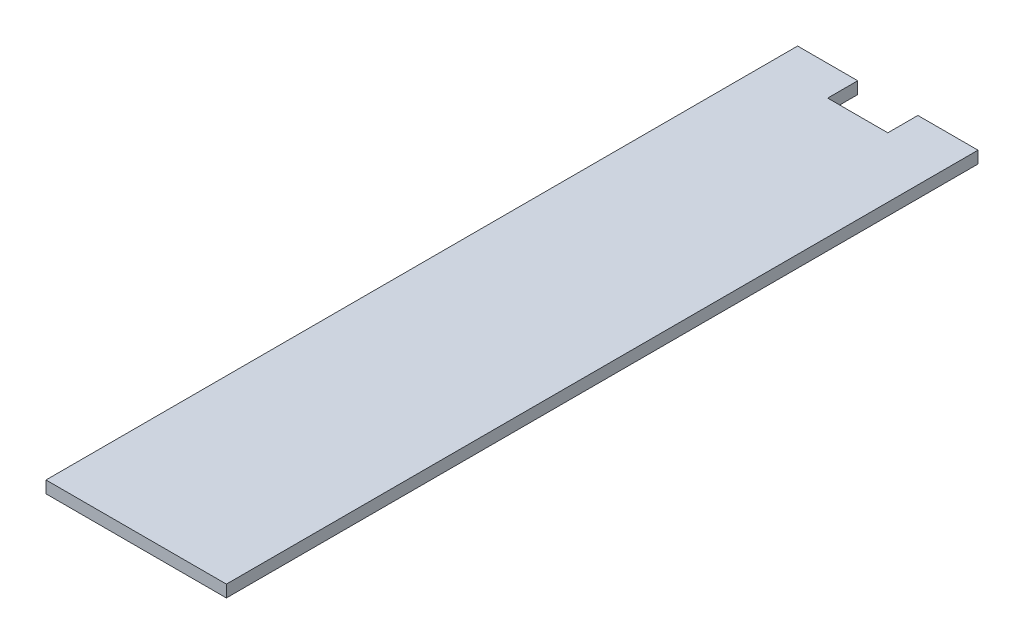
SolidWorks part; units mm, degrees
material "Mahogany"
ref_plane "Front" through (0, 0, 0) normal (0, 0, 1) x (1, 0, 0)
ref_plane "Top" through (0, 0, 0) normal (0, 1, 0) x (1, 0, 0)
ref_plane "Right" through (0, 0, 0) normal (1, 0, 0) x (0, 0, -1)
sketch "Sketch1" plane through (0, 0, 0) normal (0, 1, 0) x (1, 0, 0)
  line L0 (12.7, 158.75) -> (25.4, 158.75) construction
  line L1 (0, 0) -> (38.1, 0)
  line L2 (0, 0) -> (0, 152.4)
  line L3 (0, 152.4) -> (38.1, 152.4)
  line L4 (38.1, 0) -> (38.1, 152.4)
  line L5 (0, 152.4) -> (12.7, 152.4)
  line L6 (0, 152.4) -> (0, 158.75)
  line L7 (0, 158.75) -> (12.7, 158.75)
  line L8 (12.7, 152.4) -> (12.7, 158.75)
  line L9 (38.1, 152.4) -> (25.4, 152.4)
  line L10 (38.1, 152.4) -> (38.1, 158.75)
  line L11 (38.1, 158.75) -> (25.4, 158.75)
  line L12 (25.4, 152.4) -> (25.4, 158.75)
  dimension "D1" = 38.1
  dimension "D2" = 152.4
  dimension "D3" = 6.35
extrude "Boss-Extrude1" add sketch "Sketch1" along normal blind 2.54 contours L1 L4 L3 L2 | L3 L8 L7 L6 | L12 L3 L10 L11
